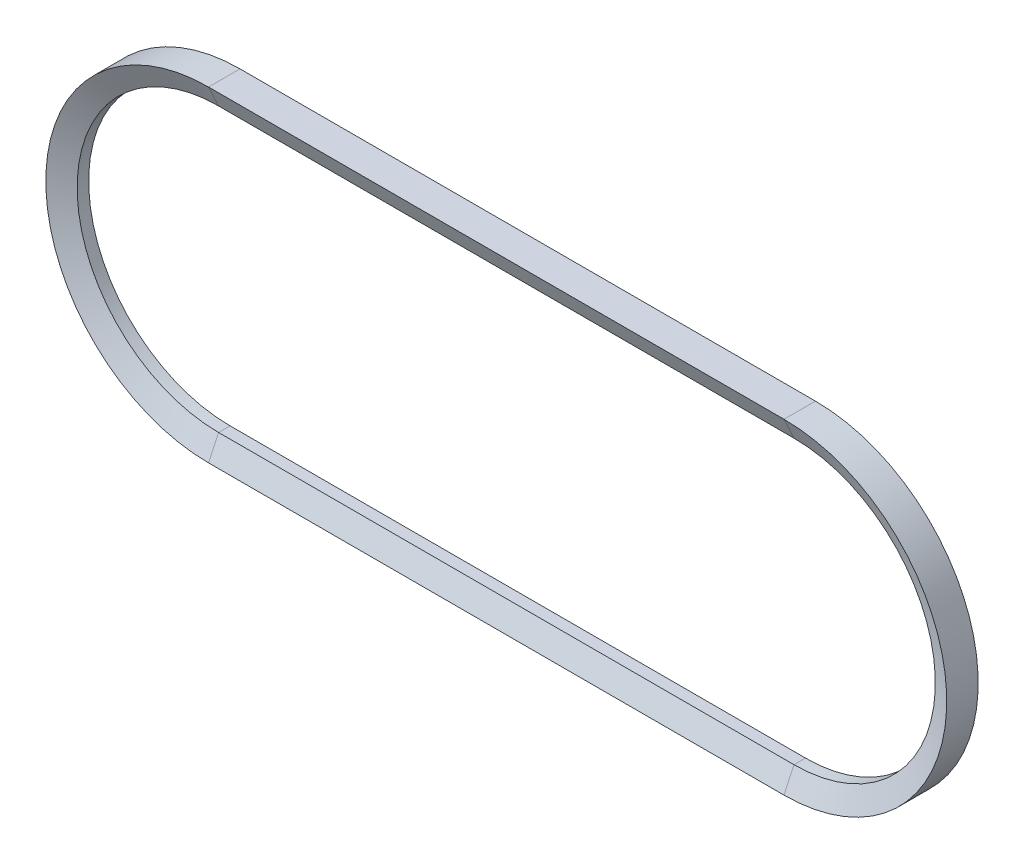
SolidWorks part; units mm, degrees
ref_plane "Alzado" through (0, 0, 0) normal (0, 0, 1) x (1, 0, 0)
ref_plane "Planta" through (0, 0, 0) normal (0, 1, 0) x (1, 0, 0)
ref_plane "Vista lateral" through (0, 0, 0) normal (1, 0, 0) x (0, 0, -1)
sketch "Croquis2" plane through (0, 0, 0) normal (0, 0, 1) x (1, 0, 0)
  line L0 (0, 0) -> (1, 0) construction
  line L1 (0, 0) -> (0, 1) construction
  line L2 (0, 172) -> (700, 172)
  line L3 (700, -172) -> (0, -172)
  arc A0 (0, -172) -> (0, 172) centre (0, 0) cw
  arc A1 (700, 172) -> (700, -172) centre (700, 0) cw
sketch "Croquis3" plane through (0, 0, 0) normal (1, 0, 0) x (0, 0, -1)
  line L0 (-7, 172) -> (7, 172)
  line L1 (7, 172) -> (19.124, 198)
  line L2 (-7, 172) -> (-19.124, 198)
  line L3 (-19.124, 198) -> (19.124, 198)
  point P4 (0, 172)
  dimension "D1" = 38.248
  dimension "D2" = 14
  dimension "D3" = 26
  dimension "D4" = 65
sweep "Barrer1" add profiles "Croquis3" path "Croquis2"
